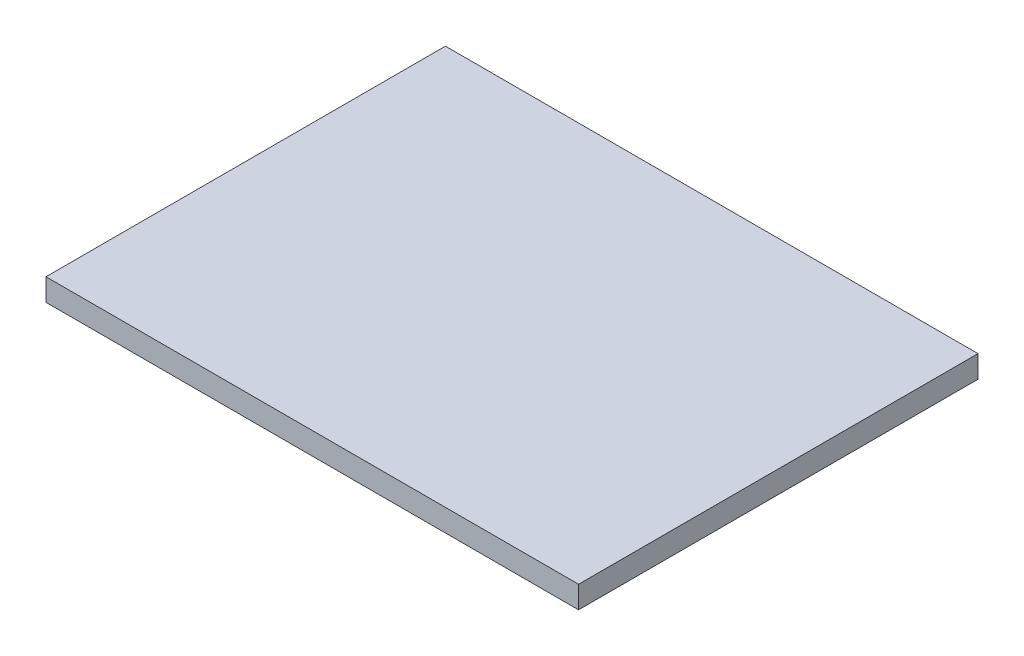
SolidWorks part; units mm, degrees
ref_plane "Front Plane" through (0, 0, 0) normal (0, 0, 1) x (1, 0, 0)
ref_plane "Top Plane" through (0, 0, 0) normal (0, 1, 0) x (1, 0, 0)
ref_plane "Right Plane" through (0, 0, 0) normal (1, 0, 0) x (0, 0, -1)
sketch "Sketch1" plane through (0, 0, 0) normal (0, 1, 0) x (1, 0, 0)
  line L1 (-60, 45) -> (60, 45)
  line L2 (-60, 45) -> (-60, -45)
  line L3 (-60, -45) -> (60, -45)
  line L4 (60, 45) -> (60, -45)
  point P4 (0, -45)
  point P6 (-60, 0)
  dimension "D1" = 120
  dimension "D2" = 90
extrude "Boss-Extrude1" add sketch "Sketch1" along normal blind 5
